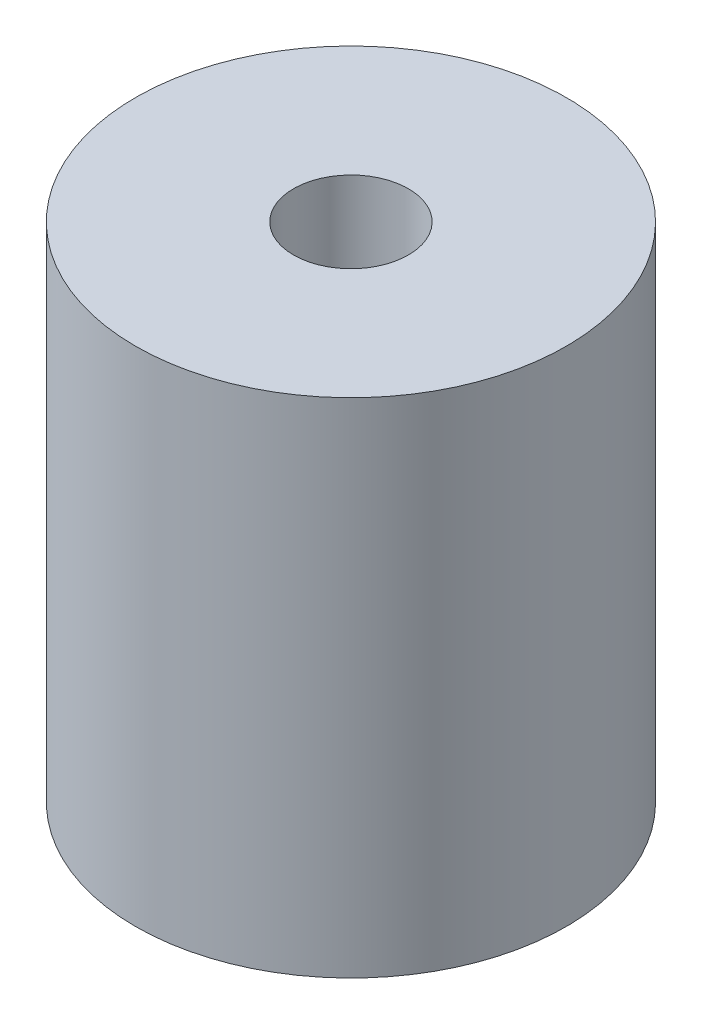
SolidWorks part; units mm, degrees
ref_plane "Front Plane" through (0, 0, 0) normal (0, 0, 1) x (1, 0, 0)
ref_plane "Top Plane" through (0, 0, 0) normal (0, 1, 0) x (1, 0, 0)
ref_plane "Right Plane" through (0, 0, 0) normal (1, 0, 0) x (0, 0, -1)
sketch "Sketch1" plane through (0, 0, 0) normal (0, 1, 0) x (1, 0, 0)
  circle A0 centre (0, 0) radius 6.35
  circle A1 centre (0, 0) radius 15
extrude "Boss-Extrude1" add sketch "Sketch1" along normal blind 11
sketch "Sketch2" plane through (0, 11, 0) normal (0, 1, 0) x (1, 0, 0)
  circle A0 centre (0, 0) radius 15
extrude "Boss-Extrude2" add sketch "Sketch2" along normal blind 13
sketch "Sketch3" plane through (0, 24, 0) normal (0, 1, 0) x (1, 0, 0)
  circle A0 centre (0, 0) radius 4
  circle A1 centre (0, 0) radius 15
extrude "Boss-Extrude3" add sketch "Sketch3" along normal blind 11
